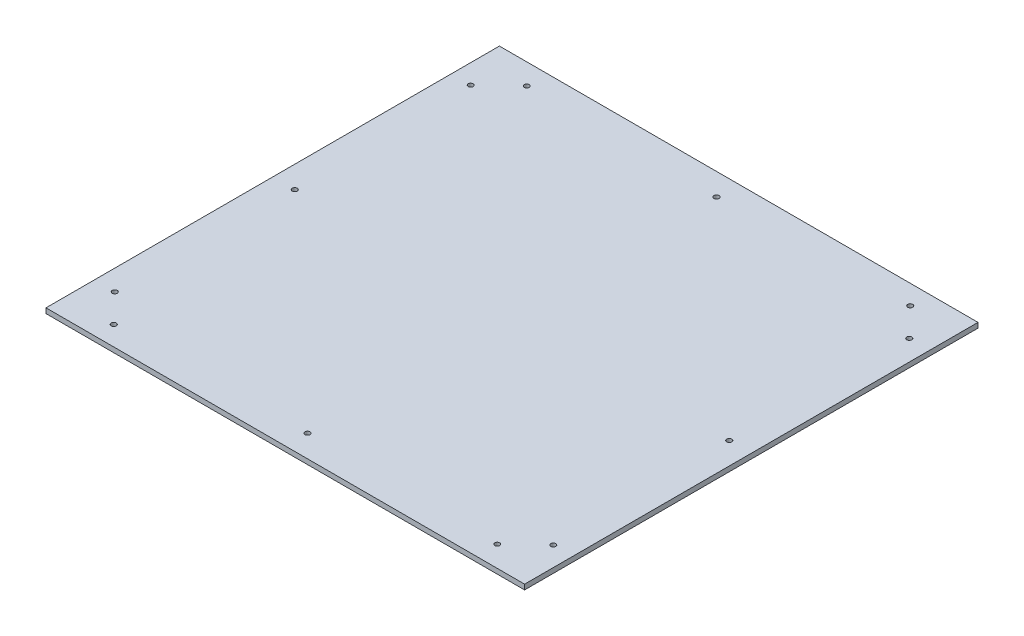
SolidWorks part; units mm, degrees
ref_plane "Front" through (0, 0, 0) normal (0, 0, 1) x (1, 0, 0)
ref_plane "Top" through (0, 0, 0) normal (0, 1, 0) x (1, 0, 0)
ref_plane "Right" through (0, 0, 0) normal (1, 0, 0) x (0, 0, -1)
sketch "Sketch1" plane through (0, 0, 0) normal (0, 1, 0) x (1, 0, 0)
  line L1 (-241.3, 228.6) -> (241.3, 228.6)
  line L2 (-241.3, 228.6) -> (-241.3, -228.6)
  line L3 (-241.3, -228.6) -> (241.3, -228.6)
  line L4 (241.3, 228.6) -> (241.3, -228.6)
  line L5 (-241.3, 228.6) -> (241.3, -228.6) construction
  line L6 (-241.3, -228.6) -> (241.3, 228.6) construction
  point P0 (0, 0)
  dimension "D1" = 482.6
  dimension "D2" = 457.2
extrude "Boss-Extrude1" add sketch "Sketch1" along normal blind 5.08
sketch "Sketch2" plane through (0, 5.08, 0) normal (0, 1, 0) x (1, 0, 0)
  line L0 (0, -2.794) -> (0, 2.794) construction
  line L1 (-241.3, 228.6) -> (241.3, -228.6) construction
  line L2 (241.3, 228.6) -> (-241.3, -228.6) construction
  line L3 (241.3, -228.6) -> (241.3, 228.6) construction
  line L4 (241.3, 228.6) -> (-241.3, 228.6) construction
  line L5 (-241.3, 228.6) -> (-241.3, -228.6) construction
  line L9 (-241.3, -228.6) -> (241.3, -228.6) construction
  line L10 (-2.794, 0) -> (2.794, 0) construction
  circle A8 centre (-192.659, 207.5383) radius 2.4765
  circle A10 centre (192.659, -207.5383) radius 2.4765
  circle A12 centre (-221.615, 179.959) radius 2.4765
  circle A14 centre (221.615, -179.959) radius 2.4765
  circle A16 centre (220.6244, 179.959) radius 2.54
  circle A17 centre (192.659, 208.915) radius 2.54
  circle A18 centre (-192.659, -208.915) radius 2.54
  circle A19 centre (-220.6244, -179.959) radius 2.54
  circle A20 centre (-219.075, 0) radius 2.54
  circle A22 centre (219.075, 0) radius 2.54
  circle A24 centre (0, 219.075) radius 2.54 [skipped]
  circle A25 centre (0, -219.075) radius 2.54 [skipped]
  circle A26 centre (0, -206.248) radius 2.54
  circle A27 centre (0, 206.248) radius 2.54
  point P45 (0, 0)
  dimension "D2" = 21.0617
  dimension "D3" = 48.641
  dimension "D1" = 4.953
  dimension "D4" = 4.953
  dimension "D5" = 48.641
  dimension "D6" = 19.685
  dimension "D7" = 19.685
  dimension "D9" = 5.08
  dimension "D10" = 5.08
  dimension "D13" = 5.08
  dimension "D14" = 20.6756
  dimension "D15" = 48.641
  dimension "D16" = 19.685
  dimension "D18" = 5.08
  dimension "D19" = 21.0617
  dimension "D20" = 48.641
  dimension "D21" = 19.685
  dimension "D22" = 48.641
  dimension "D23" = 5.08
  dimension "D24" = 22.225
  dimension "D26" = 5.08
  dimension "D27" = 22.352
  dimension "D28" = 5.08
  dimension "D29" = 22.352
  dimension "D8" = 48.641
  dimension "D11" = 20.6756
  dimension "D12" = 48.641
  dimension "D17" = 48.641
  dimension "D25" = 4
extrude "Cut-Extrude1" cut sketch "Sketch2" against normal through all
